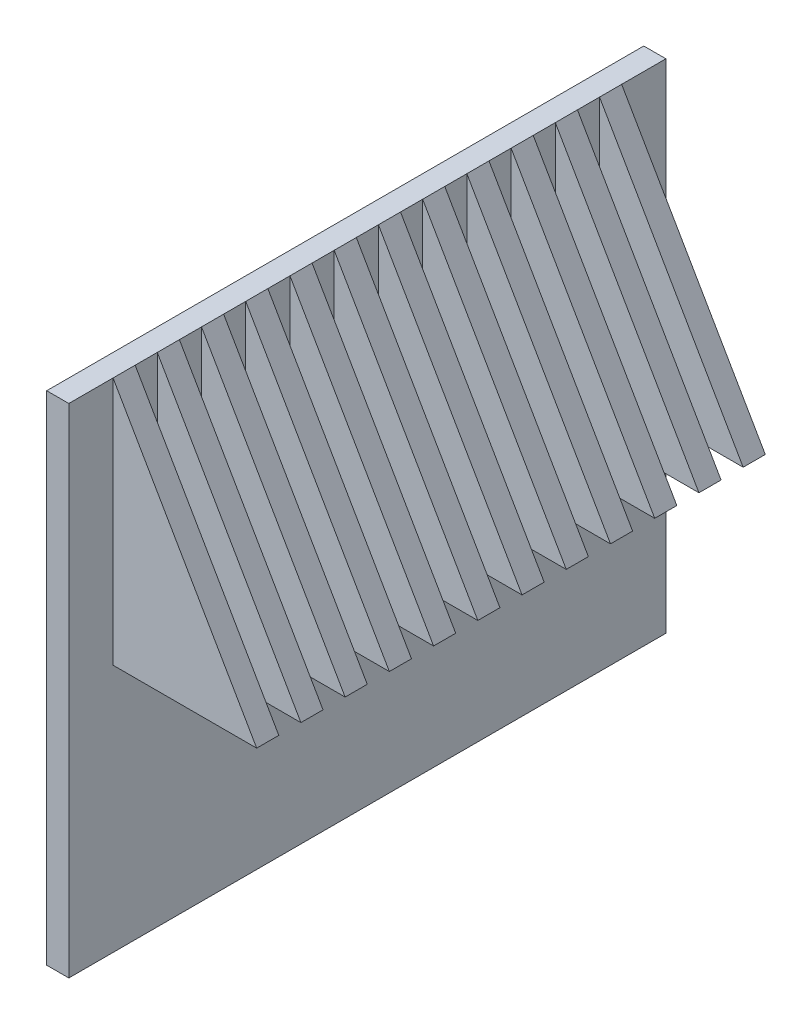
SolidWorks part; units mm, degrees
material "A286 Iron Base Superalloy"
ref_plane "Front Plane" through (0, 0, 0) normal (0, 0, 1) x (1, 0, 0)
ref_plane "Top Plane" through (0, 0, 0) normal (0, 1, 0) x (1, 0, 0)
ref_plane "Right Plane" through (0, 0, 0) normal (1, 0, 0) x (0, 0, -1)
sketch "Sketch2" plane through (0, 0, 0) normal (1, 0, 0) x (0, 0, -1)
  line L1 (0, 0) -> (270, 0)
  line L2 (0, 0) -> (0, 225)
  line L3 (0, 225) -> (270, 225)
  line L4 (270, 0) -> (270, 225)
  dimension "D1" = 270
  dimension "D2" = 225
extrude "Boss-Extrude1" add sketch "Sketch2" along normal blind 10
sketch "Sketch4" plane through (0, 0, 0) normal (0, 0, 1) x (1, 0, 0)
  line L0 (10, 225) -> (74.9519, 112.5)
  line L1 (10, 225) -> (10, 0) construction
  line L2 (10, 225) -> (10, 112.5)
  line L3 (10, 112.5) -> (74.9519, 112.5)
  dimension "D1" = 30
  dimension "D2" = 112.5
extrude "Boss-Extrude4" add sketch "Sketch4" against normal up to vertex (270 mm away) up to point (10, 225, -270)
sketch "Sketch5" plane through (0, 112.5, 0) normal (0, -1, 0) x (1, 0, 0)
  line L0 (10, -270) -> (10, -260)
  line L1 (10, -270) -> (10, 0) construction
  line L2 (10, -260) -> (74.9519, -260)
  line L3 (74.9519, -270) -> (74.9519, 0) construction
  line L4 (10, -250) -> (74.9519, -250)
  line L5 (10, -240) -> (74.9519, -240)
  line L6 (10, -230) -> (74.9519, -230)
  line L7 (10, -220) -> (74.9519, -220)
  line L8 (10, -260) -> (74.9519, -260)
  line L9 (10, -260) -> (10, -270)
  line L10 (10, -270) -> (74.9519, -270)
  line L11 (74.9519, -260) -> (74.9519, -270)
  line L12 (10, -210) -> (74.9519, -210)
  line L13 (10, -200) -> (74.9519, -200)
  line L14 (10, -190) -> (74.9519, -190)
  line L15 (10, -180) -> (74.9519, -180)
  line L16 (10, -170) -> (74.9519, -170)
  line L17 (10, -160) -> (74.9519, -160)
  line L18 (10, -150) -> (74.9519, -150)
  line L19 (10, -140) -> (74.9519, -140)
  line L20 (10, -130) -> (74.9519, -130)
  line L21 (10, -120) -> (74.9519, -120)
  line L22 (10, -110) -> (74.9519, -110)
  line L23 (10, -100) -> (74.9519, -100)
  line L24 (10, -90) -> (74.9519, -90)
  line L25 (10, -80) -> (74.9519, -80)
  line L26 (10, -70) -> (74.9519, -70)
  line L27 (10, -60) -> (74.9519, -60)
  line L28 (10, -50) -> (74.9519, -50)
  line L29 (10, -40) -> (74.9519, -40)
  line L30 (10, -30) -> (74.9519, -30)
  line L31 (10, -20) -> (74.9519, -20)
  line L32 (10, -10) -> (74.9519, -10)
  line L33 (10, 0) -> (74.9519, 0)
  line M2 (74.9519, 0) -> (10, 0)
  line M3 (10, 0) -> (10, -270)
  line M4 (10, -270) -> (74.9519, -270)
  line M5 (74.9519, -270) -> (74.9519, 0)
  dimension "D1" = 10
  dimension "D3" = 20
  dimension "D2" = 27
extrude "Cut-Extrude2" cut sketch "Sketch5" against normal through all contours L2 M3 M4 M5 | L4 L2 M3 M5 | L6 L5 M3 M5 | L12 L7 M3 M5 | L14 L13 M3 M5 | L16 L15 M3 M5 | L18 L17 M3 M5 | L20 L19 M3 M5 | L22 L21 M3 M5 | L24 L23 M3 M5 | L26 L25 M3 M5 | L28 L27 M3 M5 | L30 L29 M3 M5 | L32 L31 M3 M5 | L32 M3 M5 M2
